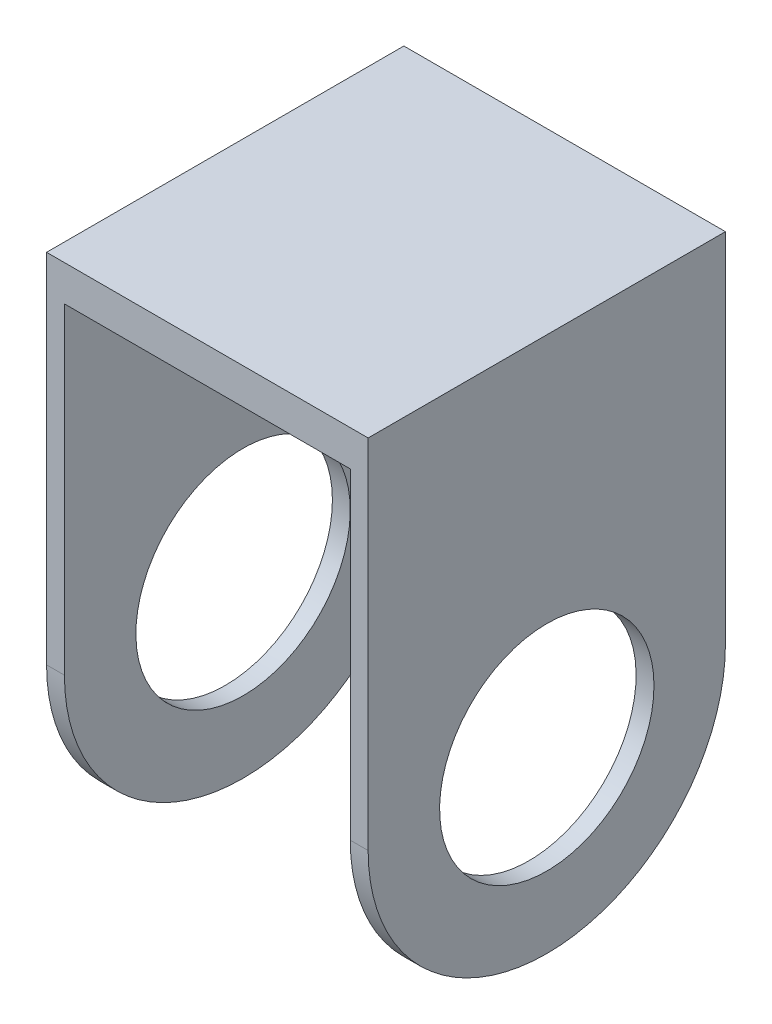
SolidWorks part; units mm, degrees
ref_plane "Front Plane" through (0, 0, 0) normal (0, 0, 1) x (1, 0, 0)
ref_plane "Top Plane" through (0, 0, 0) normal (0, 1, 0) x (1, 0, 0)
ref_plane "Right Plane" through (0, 0, 0) normal (1, 0, 0) x (0, 0, -1)
sketch "Sketch1" plane through (0, 0, 0) normal (1, 0, 0) x (0, 0, -1)
  line L0 (-11.6442, 4.3997) -> (-11.6442, 14.3997)
  line L1 (-1.6442, 14.3997) -> (-1.6442, 4.3997)
  line L2 (-11.6442, 14.3997) -> (-1.6442, 14.3997)
  arc A0 (-1.6442, 4.3997) -> (-11.6442, 4.3997) centre (-6.6442, 4.3997) cw
  circle A1 centre (-6.6442, 4.3997) radius 3
  point P6 (0, 0)
  point P7 (0, 0)
  dimension "D1" = 5
  dimension "D2" = 6
  dimension "D3" = 10
  dimension "D4" = 10
extrude "Boss-Extrude1" add sketch "Sketch1" along normal blind 9
sketch "Sketch3" plane through (0, 0, 1.6442) normal (0, 0, -1) x (-1, 0, 0)
  line L0 (-0.5, 13.3997) -> (-8.5, 13.3997)
  line L1 (-0.5, 13.3997) -> (-0.5, -1.5264)
  line L2 (-8.5, 13.3997) -> (-8.5, -1.5264)
  line L3 (-0.5, -1.5264) -> (-8.5, -1.5264)
  line L5 (-9, 14.3997) -> (0, 14.3997) construction
  line L6 (-9, 14.3997) -> (-9, 4.3997) construction
  line L7 (0, 14.3997) -> (0, 4.3997) construction
  point P6 (0, 0)
  dimension "D1" = 1
  dimension "D2" = 0.5
  dimension "D3" = 0.5
extrude "Cut-Extrude1" cut sketch "Sketch3" against normal blind 12
